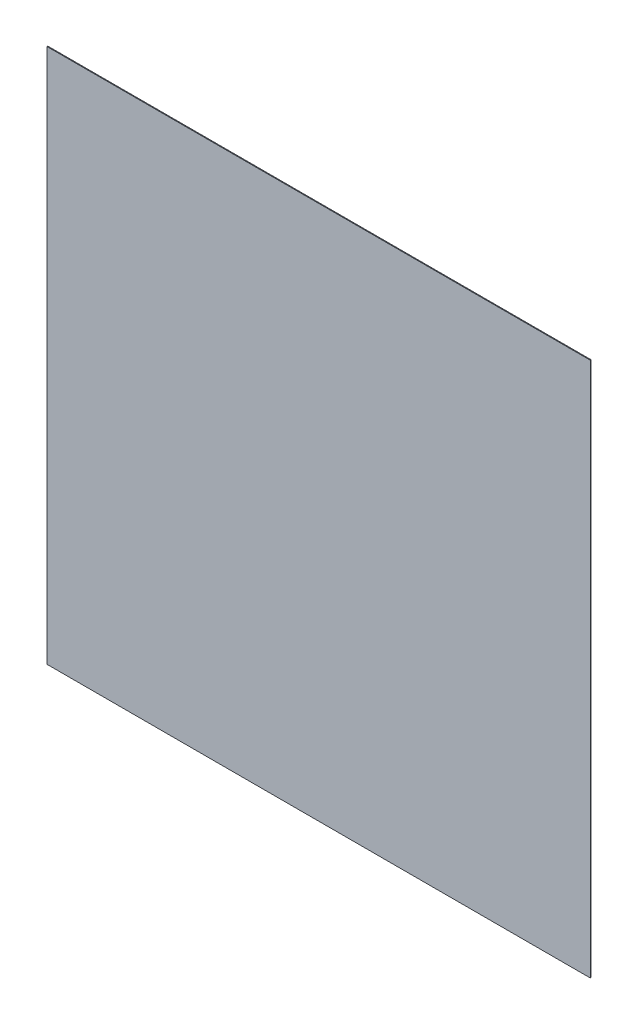
SolidWorks part; units mm, degrees
ref_plane "Alzado" through (0, 0, 0) normal (0, 0, 1) x (1, 0, 0)
ref_plane "Planta" through (0, 0, 0) normal (0, 1, 0) x (1, 0, 0)
ref_plane "Vista lateral" through (0, 0, 0) normal (1, 0, 0) x (0, 0, -1)
sketch "Croquis1" plane through (0, 0, 0) normal (0, 0, 1) x (1, 0, 0)
  line L1 (-650, 640) -> (650, 640)
  line L2 (-650, 640) -> (-650, -640)
  line L3 (-650, -640) -> (650, -640)
  line L4 (650, 640) -> (650, -640)
  line L5 (-650, 640) -> (650, -640) construction
  line L6 (-650, -640) -> (650, 640) construction
  point P0 (0, 0)
  dimension "D1" = 1300
  dimension "D2" = 1280
extrude "Saliente-Extruir1" add sketch "Croquis1" along normal blind 1.92
